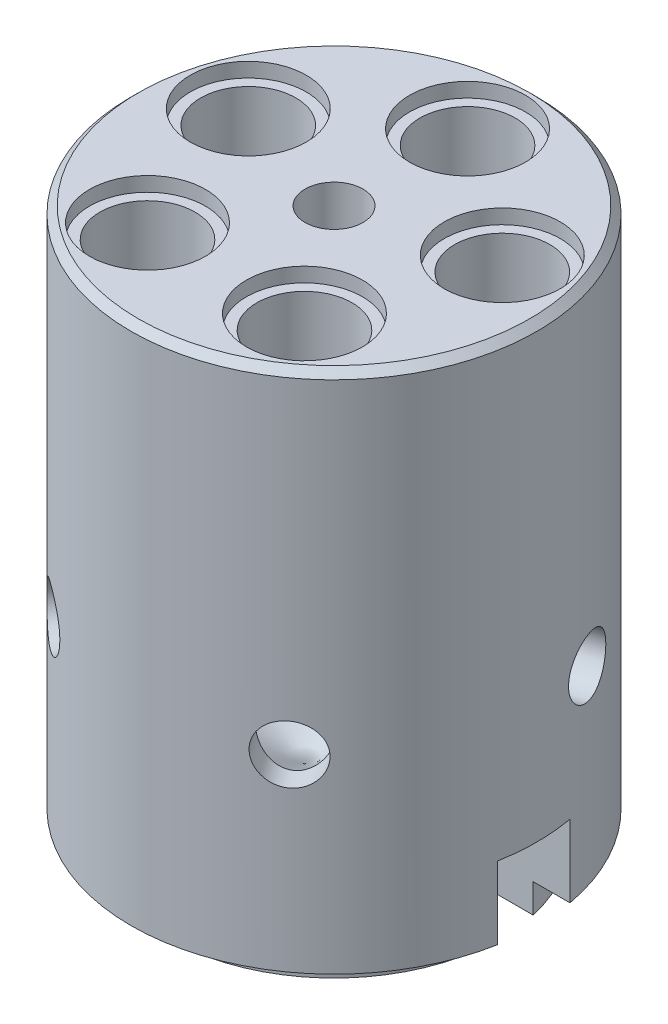
SolidWorks part; units mm, degrees
ref_plane "Plan de face" through (0, 0, 0) normal (0, 0, 1) x (1, 0, 0)
ref_plane "Plan de dessus" through (0, 0, 0) normal (0, 1, 0) x (1, 0, 0)
ref_plane "Plan de droite" through (0, 0, 0) normal (1, 0, 0) x (0, 0, -1)
sketch "Esquisse1" plane through (0, 0, 0) normal (0, 0, 1) x (1, 0, 0)
  line L1 (0, 0) -> (14, 0)
  line L2 (0, 0) -> (0, 38)
  line L3 (0, 38) -> (14, 38)
  line L4 (14, 0) -> (14, 38)
  dimension "D1" = 38
  dimension "D2" = 14
revolve "Révolution1" add sketch "Esquisse1" angle 360 about L2
sketch "Esquisse2" plane through (0, 38, 0) normal (0, 1, 0) x (-1, 0, 0)
  circle A0 centre (0, 0) radius 2
  dimension "D1" = 4
extrude "Enlèv. mat.-Extru.1" cut sketch "Esquisse2" against normal through all
hole_wizard "Chambrage pour vis à tête hexagonale M51" positions "Esquisse4" profile "Esquisse3" counterbore size "M5" standard "ISO"
sketch "Esquisse4" plane through (0, 38, 0) normal (0, 1, 0) x (-1, 0, 0)
  circle A0 centre (0, 0) radius 2 construction
  point P0 (0, -9.21)
  dimension "D1" = 9.21
  dimension "D2" = 0
sketch "Esquisse3" plane through (0, 38, -9.21) normal (1, 0, 0) x (0, 0, 1)
  line L0 (0, 0) -> (0, 26.8966)
  line L1 (0, 26.8966) -> (3.285, 25)
  line L2 (3.285, 25) -> (3.285, 1)
  line L3 (3.285, 1) -> (4, 1)
  line L4 (4, 1) -> (4, 0)
  line L5 (4, 0) -> (0, 0)
  line L10 (0, 26.8966) -> (-3.285, 25) construction
  line L11 (0, -6.35) -> (0, 107.95) construction
  dimension "Diamètre du perçage" = 6.57
  dimension "Profondeur du perçage" = 25
  dimension "Diamètre du chambrage" = 8
  dimension "Profondeur du chambrage" = 1
  dimension "Angle de pointe" = 120
pattern_circular "Répétition circulaire1" count 5 over 360 about axis through (0, 0, 0) along (0, 1, 0) of "Chambrage pour vis à tête hexagonale M51"
chamfer "Chanfrein1" distance 0.5 angle 45 1 edges at (0, 38, -14)
sketch "Esquisse5" plane through (0, 0, 0) normal (0, -1, 0) x (1, 0, 0)
  circle A0 centre (0, 0) radius 11.5
  circle A1 centre (0, 0) radius 15
  dimension "D1" = 23
  dimension "D2" = 30
extrude "Enlèv. mat.-Extru.2" cut sketch "Esquisse5" against normal blind 2
sketch "Esquisse7" plane through (0, 0, 0) normal (0, -1, 0) x (1, 0, 0)
  line L1 (-16, 2.5) -> (16, 2.5)
  line L2 (-16, 2.5) -> (-16, -2.5)
  line L3 (-16, -2.5) -> (16, -2.5)
  line L4 (16, 2.5) -> (16, -2.5)
  dimension "D1" = 5
  dimension "D2" = 2.5
  dimension "D3" = 32
  dimension "D4" = 16
extrude "Enlèv. mat.-Extru.3" cut sketch "Esquisse7" against normal blind 7
ref_plane "Plan1" through (0, 0, -14) normal (0, 0, -1) x (-1, 0, 0)
sketch "Esquisse8" plane through (0, 0, -14) normal (0, 0, -1) x (-1, 0, 0)
  line L0 (-11.225, 0) -> (11.225, 0) construction
  circle A0 centre (0, 15) radius 2
  dimension "D2" = 4
  dimension "D1" = 15
  dimension "D3" = 0
extrude "Enlèv. mat.-Extru.4" cut sketch "Esquisse8" against normal up to next
pattern_circular "Répétition circulaire2" count 5 over 360 about axis through (0, 0, 0) along (0, -1, 0) of "Enlèv. mat.-Extru.4"
